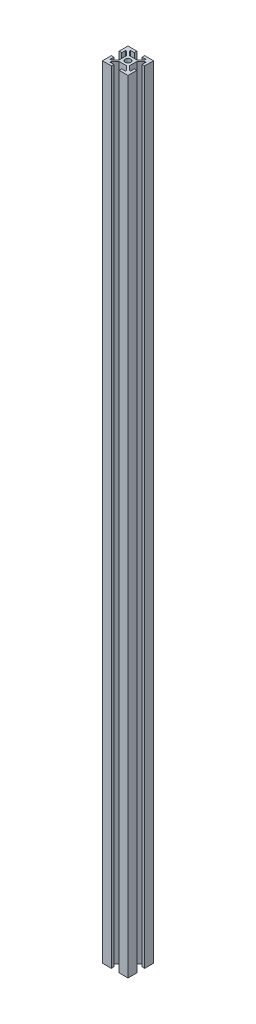
SolidWorks part; units mm, degrees
ref_plane "Front" through (0, 0, 0) normal (0, 0, 1) x (1, 0, 0)
ref_plane "Top" through (0, 0, 0) normal (0, 1, 0) x (1, 0, 0)
ref_plane "Right" through (0, 0, 0) normal (1, 0, 0) x (0, 0, -1)
sketch "스케치1" plane through (0, 0, 0) normal (0, 1, 0) x (1, 0, 0)
  line L0 (3.1, 8) -> (6, 8)
  line L1 (-10.001, 9.999) -> (-3.1, 9.999)
  line L2 (-10.001, 9.999) -> (-10.001, 3.1)
  line L3 (-10.001, -9.999) -> (-3.1, -9.999)
  line L4 (10.001, 9.999) -> (10.001, 3.1)
  line L5 (-10.001, 9.999) -> (-1.5204, 1.5201) construction
  line L6 (-10.001, -9.999) -> (-1.5204, -1.5201) construction
  line L11 (-7, -7) -> (-1.5203, -1.5203) construction
  line L12 (-7, 7) -> (-1.5203, 1.5203) construction
  line L15 (-3.1, 9.999) -> (-3.1, 8)
  line L17 (3.1, 9.999) -> (3.1, 8)
  line L18 (8, -3.1) -> (8, -6)
  line L27 (-3.1, 8) -> (-6, 8)
  line L28 (6, 8) -> (6, 7)
  line L30 (0, 4) -> (3, 4)
  line L31 (3, 4) -> (6, 7)
  line L32 (-6, 8) -> (-6, 7)
  line L33 (-6, 7) -> (-3, 4)
  line L34 (0, 4) -> (-3, 4)
  line L35 (3.1, 9.999) -> (10.001, 9.999)
  line L36 (10.001, 3.1) -> (8, 3.1)
  line L37 (10.001, -3.1) -> (8, -3.1)
  line L38 (8, 3.1) -> (8, 6)
  line L39 (8, -6) -> (7, -6)
  line L40 (4, 0) -> (4, -3)
  line L41 (4, -3) -> (7, -6)
  line L42 (8, 6) -> (7, 6)
  line L43 (7, 6) -> (4, 3)
  line L44 (4, 0) -> (4, 3)
  line L45 (-3.1, -8) -> (-6, -8)
  line L47 (3.1, -9.999) -> (3.1, -8)
  line L48 (-3.1, -9.999) -> (-3.1, -8)
  line L49 (3.1, -8) -> (6, -8)
  line L50 (-6, -8) -> (-6, -7)
  line L51 (0, -4) -> (-3, -4)
  line L52 (-3, -4) -> (-6, -7)
  line L53 (6, -8) -> (6, -7)
  line L54 (6, -7) -> (3, -4)
  line L55 (0, -4) -> (3, -4)
  line L56 (-8, 3.1) -> (-8, 6)
  line L58 (-10.001, -3.1) -> (-8, -3.1)
  line L59 (-10.001, 3.1) -> (-8, 3.1)
  line L60 (-8, -3.1) -> (-8, -6)
  line L61 (-8, 6) -> (-7, 6)
  line L62 (-4, 0) -> (-4, 3)
  line L63 (-4, 3) -> (-7, 6)
  line L64 (-8, -6) -> (-7, -6)
  line L65 (-7, -6) -> (-4, -3)
  line L66 (-4, 0) -> (-4, -3)
  line L67 (-10.001, -3.1) -> (-10.001, -9.999)
  line L69 (3.1, -9.999) -> (10.001, -9.999)
  line L72 (10.001, -3.1) -> (10.001, -9.999)
  line L73 (1.5203, -1.5203) -> (7, -7) construction
  line L74 (1.5204, -1.5201) -> (10.001, -9.999) construction
  line L75 (1.5203, 1.5203) -> (7, 7) construction
  line L76 (1.5204, 1.5201) -> (10.001, 9.999) construction
  circle A4 centre (0, 0) radius 2.15
  point P0 (0, 0)
  point P6 (0, 0)
  point P21 (0, 0)
  point P22 (0, 10)
  point P31 (0, 0)
  point P40 (10, 0)
  point P46 (0, 0)
  point P53 (0, -10)
  point P59 (0, 0)
  point P66 (-10, 0)
  point P72 (0, 0)
  dimension "D1" = 4
extrude "보스-돌출1" add sketch "스케치1" along normal blind 612.6
sketch "스케치3" plane through (10.001, 0, 0) normal (1, 0, 0) x (0, 0, -1)
  line L0 (0, 0) -> (0, 612.6) construction
  line L1 (-3, 612.6) -> (3, 612.6) construction
  circle A0 centre (0, 306.3) radius 3
extrude "컷-돌출1" cut sketch "스케치3" against normal blind 26
